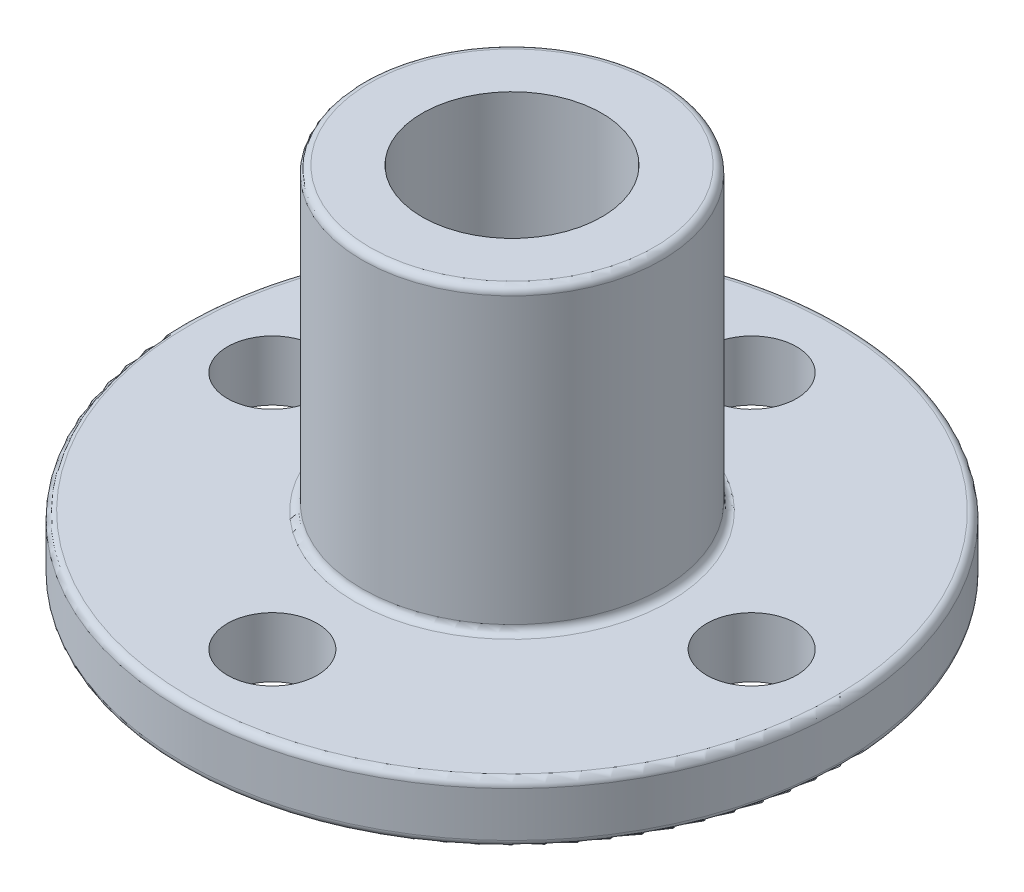
SolidWorks part; units mm, degrees
ref_plane "正面" through (0, 0, 0) normal (0, 0, 1) x (1, 0, 0)
ref_plane "平面" through (0, 0, 0) normal (0, 1, 0) x (1, 0, 0)
ref_plane "右側面" through (0, 0, 0) normal (1, 0, 0) x (0, 0, -1)
sketch "ｽｹｯﾁ1" plane through (0, 0, 0) normal (0, 1, 0) x (1, 0, 0)
  circle A0 centre (0, 0) radius 11
  dimension "D1" = 22
extrude "ﾎﾞｽ - 押し出し1" add sketch "ｽｹｯﾁ1" along normal blind 2
sketch "ｽｹｯﾁ2" plane through (0, 2, 0) normal (0, 1, 0) x (1, 0, 0)
  circle A0 centre (0, 0) radius 5
  dimension "D1" = 10
extrude "ﾎﾞｽ - 押し出し2" add sketch "ｽｹｯﾁ2" along normal blind 10
sketch "ｽｹｯﾁ3" plane through (0, 12, 0) normal (0, 1, 0) x (1, 0, 0)
  circle A0 centre (0, 0) radius 3
  dimension "D1" = 6
extrude "ｶｯﾄ - 押し出し1" cut sketch "ｽｹｯﾁ3" against normal through all
sketch "ｽｹｯﾁ4" plane through (0, 0, 0) normal (0, -1, 0) x (1, 0, 0)
  circle A0 centre (0, 0) radius 8 construction
  circle A1 centre (0, 8) radius 1.5
  dimension "D1" = 16
  dimension "D2" = 3
extrude "ｶｯﾄ - 押し出し2" cut sketch "ｽｹｯﾁ4" against normal through all
pattern_circular "円形ﾊﾟﾀｰﾝ1" count 4 over 360 about axis through (0, 0, 0) along (0, 1, 0) of "ｶｯﾄ - 押し出し2"
fillet "ﾌｨﾚｯﾄ1" radius 0.25 4 edges at (0, 2, 5) (0, 12, 5) (0, 0, 11) (0, 2, 11)
